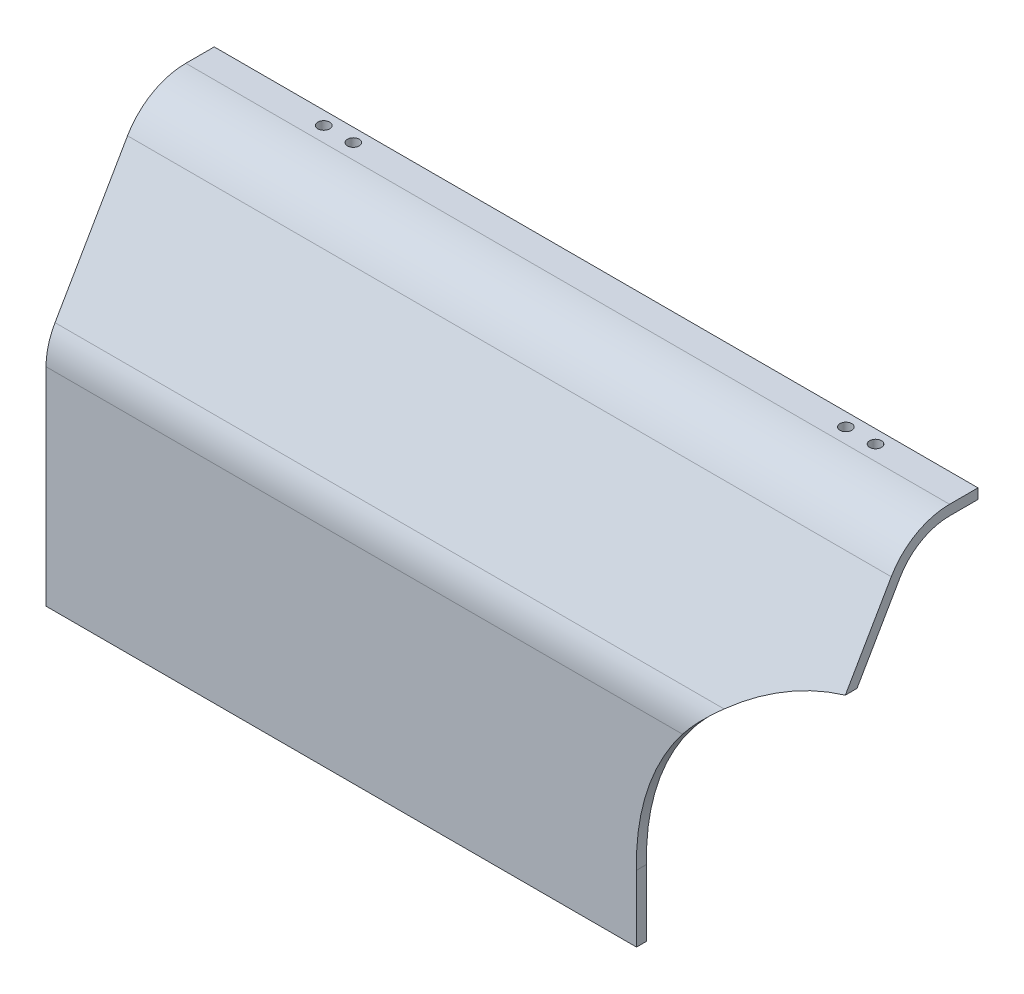
SolidWorks part; units mm, degrees
material "Acrílico (Impacto medio-alto)"
ref_plane "Alzado" through (0, 0, 0) normal (0, 0, 1) x (1, 0, 0)
ref_plane "Planta" through (0, 0, 0) normal (0, 1, 0) x (1, 0, 0)
ref_plane "Vista lateral" through (0, 0, 0) normal (1, 0, 0) x (0, 0, -1)
sketch "Croquis1" plane through (0, 0, 0) normal (1, 0, 0) x (0, 0, -1)
  line L0 (0, 0) -> (0, 66.1962)
  line L1 (0, 66.1962) -> (28.7321, 115.9615)
  line L2 (28.7321, 115.9615) -> (47, 115.9615)
  line L3 (47, 115.9615) -> (47, 118.9615)
  line L4 (47, 118.9615) -> (27, 118.9615)
  line L5 (27, 118.9615) -> (-3, 67)
  line L6 (-3, 67) -> (-3, 0)
  line L7 (-3, 0) -> (0, 0)
  line L8 (0, 66.1962) -> (29.2398, 66.1962) construction
  dimension "D1" = 3
  dimension "D2" = 3
  dimension "D3" = 3
  dimension "D4" = 67
  dimension "D5" = 60
  dimension "D6" = 20
  dimension "D7" = 60
extrude "Saliente-Extruir1" add sketch "Croquis1" along normal mid plane 227
fillet "Redondeo1" radius 20 1 edges at (0, 67, 3)
fillet "Redondeo2" radius 20 1 edges at (0, 118.9615, -27)
fillet "Redondeo3" radius 17 1 edges at (0, 115.9615, -28.7321)
fillet "Redondeo4" radius 17 1 edges at (0, 66.1962, 0)
sketch "Croquis2" plane through (0, 0, 3) normal (0, 0, 1) x (1, 0, 0)
  circle A0 centre (126.88, 22.7215) radius 70
  dimension "D1" = 140
  dimension "D2" = 13.38
  dimension "D3" = 86.24
extrude "Cortar-Extruir1" [suppressed] cut sketch "Croquis2" against normal through all
sketch "Croquis4" plane through (0, 118.9615, 0) normal (0, 1, 0) x (1, 0, 0)
  circle A0 centre (-77, 43.047) radius 1.75
  circle A1 centre (-68.2, 43.047) radius 1.75
extrude "Cortar-Extruir3" cut sketch "Croquis4" against normal blind 4
sketch "Croquis5" plane through (0, 118.9615, 0) normal (0, 1, 0) x (1, 0, 0)
  circle A0 centre (78.2, 43.047) radius 1.75
  circle A1 centre (87, 43.047) radius 1.75
  dimension "D1" = 3.5
extrude "Cortar-Extruir4" cut sketch "Croquis5" against normal blind 4
sketch "Croquis7" plane through (0, 0, 3) normal (0, 0, 1) x (1, 0, 0)
  circle A0 centre (126.9781, 21.7215) radius 65
  dimension "D1" = 130
extrude "Cortar-Extruir6" cut sketch "Croquis7" against normal through all
sketch "Croquis8" plane through (0, 0, 3) normal (0, 0, 1) x (1, 0, 0)
  line L0 (65.7149, 0) -> (62.007, 0)
  line L1 (65.7149, 0) -> (-113.5, 0) construction
  line L2 (62.007, 0) -> (62.007, 19.7814)
  arc A0 (75.6806, 61.641) -> (65.7149, 0) centre (126.9781, 21.7215) ccw construction
  arc A1 (62.007, 19.7814) -> (65.7149, 0) centre (126.9781, 21.7215) ccw
extrude "Cortar-Extruir7" cut sketch "Croquis8" against normal through all
